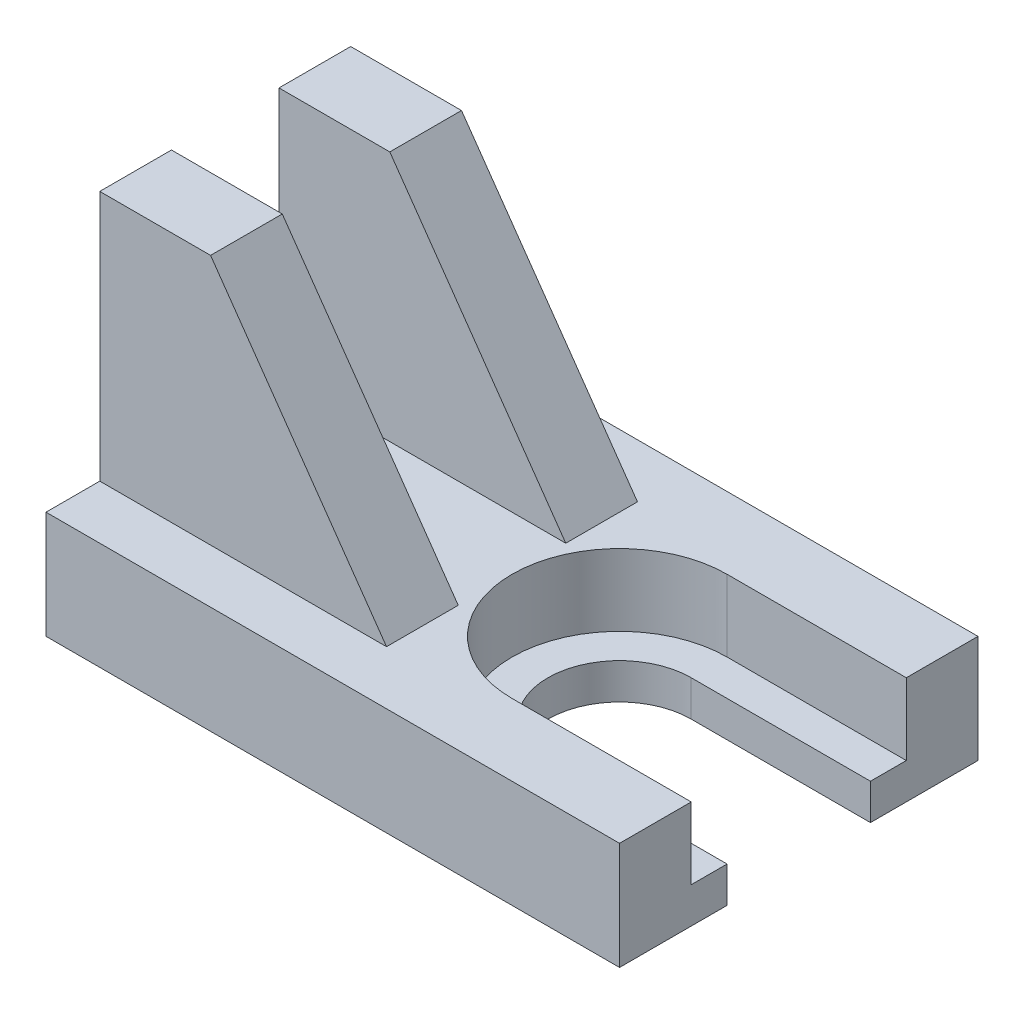
SolidWorks part; units mm, degrees
ref_plane "Front Plane" through (0, 0, 0) normal (0, 0, 1) x (1, 0, 0)
ref_plane "Top Plane" through (0, 0, 0) normal (0, 1, 0) x (1, 0, 0)
ref_plane "Right Plane" through (0, 0, 0) normal (1, 0, 0) x (0, 0, -1)
sketch "Sketch1" plane through (0, 0, 0) normal (0, 1, 0) x (1, 0, 0)
  line L1 (-40, -25) -> (40, -25)
  line L2 (-40, -25) -> (-40, 25)
  line L3 (-40, 25) -> (40, 25)
  line L4 (40, -25) -> (40, 25)
  line L5 (-40, -25) -> (40, 25) construction
  line L6 (-40, 25) -> (40, -25) construction
  point P0 (0, 0)
  dimension "D1" = 80
  dimension "D2" = 50
extrude "Boss-Extrude1" add sketch "Sketch1" along normal blind 15
sketch "Sketch6" plane through (0, 15, 0) normal (0, 1, 0) x (1, 0, 0)
  line L0 (40, -25) -> (40, 25) construction
  line L1 (40, -15) -> (15, -15)
  line L2 (40, -15) -> (40, 15)
  line L3 (40, 15) -> (15, 15)
  line L5 (-40, -25) -> (40, -25) construction
  line L6 (40, 25) -> (-40, 25) construction
  arc A0 (15, 15) -> (15, -15) centre (15, 0) ccw
  dimension "D1" = 10
  dimension "D2" = 10
  dimension "D3" = 25
extrude "Cut-Extrude2" cut sketch "Sketch6" against normal blind 10
sketch "Sketch8" plane through (0, 5, 0) normal (0, 1, 0) x (1, 0, 0)
  line L0 (40, -15) -> (40, 15) construction
  line L1 (40, -10) -> (15, -10)
  line L2 (40, -10) -> (40, 10)
  line L3 (40, 10) -> (15, 10)
  line L5 (15, -15) -> (40, -15) construction
  line L6 (40, 15) -> (15, 15) construction
  arc A0 (15, 10) -> (15, -10) centre (15, 0) ccw
  dimension "D1" = 5
  dimension "D2" = 5
extrude "Cut-Extrude3" cut sketch "Sketch8" against normal blind 10
ref_plane "Plane1" through (0, 0, 17.5) normal (0, 0, 1) x (1, 0, 0)
sketch "Sketch9" plane through (0, 0, 17.5) normal (0, 0, 1) x (1, 0, 0)
  line L0 (-40, 15) -> (-40, 50)
  line L1 (-40, 50) -> (-24.5433, 50)
  line L2 (-24.5433, 50) -> (0, 15)
  line L3 (-40, 15) -> (40, 15) construction
  line L4 (-40, 15) -> (0, 15)
  dimension "D1" = 35
  dimension "D2" = 40
  dimension "D3" = 42.7478
extrude "Boss-Extrude2" add sketch "Sketch9" against normal blind 10
mirror "Mirror1" about plane through (0, 0, 0) normal (0, 0, 1) of "Boss-Extrude2"
